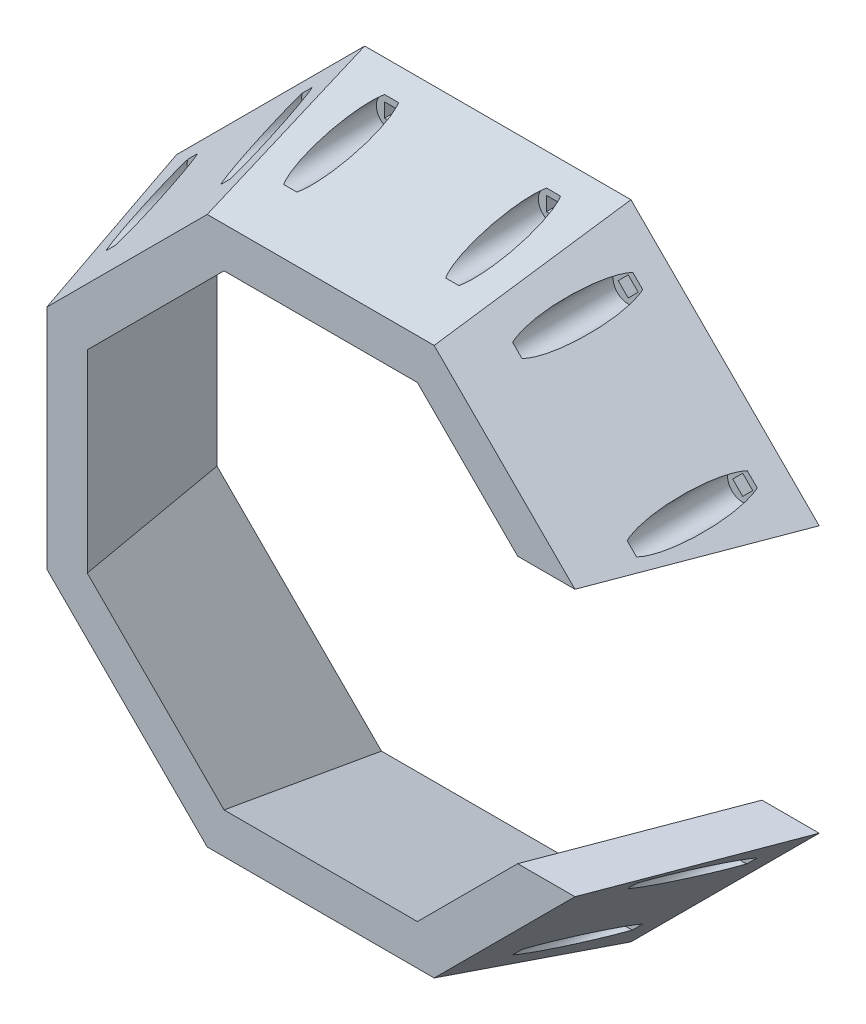
SolidWorks part; units mm, degrees
ref_plane "Plano frontal" through (0, 0, 0) normal (0, 0, 1) x (1, 0, 0)
ref_plane "Plano superior" through (0, 0, 0) normal (0, 1, 0) x (1, 0, 0)
ref_plane "Plano direito" through (0, 0, 0) normal (1, 0, 0) x (0, 0, -1)
sketch "Esboço1" plane through (0, 0, 0) normal (0, 0, 1) x (1, 0, 0)
  line L1 (63.5, -26.3026) -> (63.5, 26.3026)
  line L2 (63.5, 26.3026) -> (26.3026, 63.5)
  line L3 (26.3026, 63.5) -> (-26.3026, 63.5)
  line L4 (-26.3026, 63.5) -> (-63.5, 26.3026)
  line L5 (-63.5, 26.3026) -> (-63.5, -26.3026)
  line L6 (-63.5, -26.3026) -> (-26.3026, -63.5)
  line L7 (-26.3026, -63.5) -> (26.3026, -63.5)
  line L8 (26.3026, -63.5) -> (63.5, -26.3026)
  circle A0 centre (0, 0) radius 63.5 construction
  circle A1 centre (0, 0) radius 61.5 construction
  dimension "D1" = 127
  dimension "D2" = 2
extrude "Ressalto-extrusão1" add sketch "Esboço1" along normal blind 35 draft 15
sketch "Esboço2" plane through (0, 0, 0) normal (0, 0, 1) x (1, 0, 0)
  line L0 (63.5, 0) -> (43.8368, 0) construction
  line L1 (63.5, -26.3026) -> (63.5, 26.3026) construction
  line L3 (24.1735, 26.3026) -> (63.5, 26.3026)
  line L4 (24.1735, 26.3026) -> (24.1735, -26.3026)
  line L5 (24.1735, -26.3026) -> (63.5, -26.3026)
  line L6 (63.5, 26.3026) -> (63.5, -26.3026)
  line L7 (24.1735, 26.3026) -> (63.5, -26.3026) construction
  line L8 (24.1735, -26.3026) -> (63.5, 26.3026) construction
extrude "Corte-extrusão1" cut sketch "Esboço2" along normal blind 50
sketch "Esboço4" plane through (0, 0, 0) normal (0, 0, -1) x (-1, 0, 0)
  line L0 (-44.9013, -44.9013) -> (-42.0729, -42.0729) construction
  line L1 (-47.7297, -34.4361) -> (-49.7096, -36.416)
  line L2 (-42.0729, -40.093) -> (-44.0528, -42.0729)
  line L3 (-42.0729, -40.093) -> (-40.093, -42.0729)
  line L4 (-40.093, -42.0729) -> (-42.0729, -44.0528)
  line L5 (-44.0528, -42.0729) -> (-42.0729, -44.0528)
  line L6 (-42.0729, -40.093) -> (-42.0729, -44.0528) construction
  line L7 (-40.093, -42.0729) -> (-44.0528, -42.0729) construction
  line L8 (-47.7297, -34.4361) -> (-45.7498, -36.416)
  line L9 (-45.7498, -36.416) -> (-47.7297, -38.3959)
  line L10 (-49.7096, -36.416) -> (-47.7297, -38.3959)
  line L11 (-47.7297, -34.4361) -> (-47.7297, -38.3959) construction
  line L12 (-45.7498, -36.416) -> (-49.7096, -36.416) construction
  line L13 (-53.3866, -28.7792) -> (-55.3665, -30.7591)
  line L14 (-53.3866, -28.7792) -> (-51.4067, -30.7591)
  line L15 (-51.4067, -30.7591) -> (-53.3866, -32.739)
  line L16 (-55.3665, -30.7591) -> (-53.3866, -32.739)
  line L17 (-53.3866, -28.7792) -> (-53.3866, -32.739) construction
  line L18 (-51.4067, -30.7591) -> (-55.3665, -30.7591) construction
  line L19 (-60.9, 25.2256) -> (-59.0434, 27.0822)
  line L20 (-57.0635, 25.1023) -> (-59.0434, 27.0822)
  line L21 (-58.1, 6.6) -> (-58.1, 9.4)
  line L22 (-58.1, -1.4) -> (-58.1, 1.4)
  line L23 (-58.1, -1.4) -> (-60.9, -1.4)
  line L24 (-60.9, -1.4) -> (-60.9, 1.4)
  line L25 (-58.1, 1.4) -> (-60.9, 1.4)
  line L26 (-30.7591, -51.4067) -> (-30.7591, -55.3665) construction
  line L27 (-28.7792, -53.3866) -> (-32.739, -53.3866) construction
  line L28 (-36.416, -45.7498) -> (-36.416, -49.7096) construction
  line L29 (-34.4361, -47.7297) -> (-38.3959, -47.7297) construction
  line L30 (-42.0729, -40.093) -> (-42.0729, -44.0528) construction
  line L31 (-40.093, -42.0729) -> (-44.0528, -42.0729) construction
  line L32 (-25.2256, -60.9) -> (-27.0822, -59.0434)
  line L33 (-25.1023, -57.0635) -> (-27.0822, -59.0434)
  line L34 (-58.1, 6.6) -> (-60.9, 6.6)
  line L35 (-30.7591, -55.3665) -> (-32.739, -53.3866)
  line L36 (-30.7591, -51.4067) -> (-32.739, -53.3866)
  line L37 (-28.7792, -53.3866) -> (-30.7591, -51.4067)
  line L38 (-28.7792, -53.3866) -> (-30.7591, -55.3665)
  line L39 (-36.416, -49.7096) -> (-38.3959, -47.7297)
  line L40 (-36.416, -45.7498) -> (-38.3959, -47.7297)
  line L41 (-34.4361, -47.7297) -> (-36.416, -45.7498)
  line L42 (-34.4361, -47.7297) -> (-36.416, -49.7096)
  line L43 (0, -63.5) -> (0, -59.5) construction
  line L44 (-6.6, -58.1) -> (-9.4, -58.1)
  line L45 (1.4, -58.1) -> (-1.4, -58.1)
  line L46 (1.4, -58.1) -> (1.4, -60.9)
  line L47 (1.4, -60.9) -> (-1.4, -60.9)
  line L48 (-1.4, -58.1) -> (-1.4, -60.9)
  line L49 (1.4, -58.1) -> (-1.4, -60.9) construction
  line L50 (1.4, -60.9) -> (-1.4, -58.1) construction
  line L51 (-6.6, -58.1) -> (-6.6, -60.9)
  line L52 (-6.6, -60.9) -> (-9.4, -60.9)
  line L53 (-9.4, -58.1) -> (-9.4, -60.9)
  line L54 (-6.6, -58.1) -> (-9.4, -60.9) construction
  line L55 (-6.6, -60.9) -> (-9.4, -58.1) construction
  line L56 (-14.6, -58.1) -> (-17.4, -58.1)
  line L57 (-14.6, -58.1) -> (-14.6, -60.9)
  line L58 (-14.6, -60.9) -> (-17.4, -60.9)
  line L59 (-17.4, -58.1) -> (-17.4, -60.9)
  line L60 (-14.6, -58.1) -> (-17.4, -60.9) construction
  line L61 (-14.6, -60.9) -> (-17.4, -58.1) construction
  line L62 (-22.6, -58.1) -> (-24.0658, -58.1)
  line L63 (-22.6, -58.1) -> (-22.6, -60.9)
  line L64 (-22.6, -60.9) -> (-25.2256, -60.9)
  line L65 (-60.9, 6.6) -> (-60.9, 9.4)
  line L66 (-58.1, 9.4) -> (-60.9, 9.4)
  line L67 (-58.1, 14.6) -> (-58.1, 17.4)
  line L68 (-58.1, 14.6) -> (-60.9, 14.6)
  line L69 (-60.9, 14.6) -> (-60.9, 17.4)
  line L70 (-58.1, 17.4) -> (-60.9, 17.4)
  line L72 (-26.3026, -63.5) -> (26.3026, -63.5)
  line L73 (26.3026, -63.5) -> (63.5, -26.3026)
  line L74 (-24.0658, -58.1) -> (-25.1023, -57.0635)
  line L75 (-58.1, 22.6) -> (-58.1, 24.0658)
  line L76 (-58.1, 22.6) -> (-60.9, 22.6)
  line L77 (63.5, -26.3026) -> (63.5, 26.3026)
  line L78 (-60.9, 22.6) -> (-60.9, 25.2256)
  line L79 (-58.1, 24.0658) -> (-57.0635, 25.1023)
  line L80 (-58.1, -24.0658) -> (-57.0635, -25.1023)
  line L81 (-60.9, -22.6) -> (-60.9, -25.2256)
  line L82 (-58.1, -22.6) -> (-60.9, -22.6)
  line L83 (-58.1, -22.6) -> (-58.1, -24.0658)
  line L84 (-58.1, -17.4) -> (-60.9, -17.4)
  line L85 (-60.9, -14.6) -> (-60.9, -17.4)
  line L86 (-58.1, -14.6) -> (-60.9, -14.6)
  line L87 (-58.1, -14.6) -> (-58.1, -17.4)
  line L88 (-58.1, -9.4) -> (-60.9, -9.4)
  line L89 (-60.9, -6.6) -> (-60.9, -9.4)
  line L90 (-58.1, -6.6) -> (-60.9, -6.6)
  line L91 (-58.1, -6.6) -> (-58.1, -9.4)
  line L92 (63.5, 26.3026) -> (26.3026, 63.5)
  line L93 (26.3026, 63.5) -> (-26.3026, 63.5)
  line L94 (-57.0635, -25.1023) -> (-59.0434, -27.0822)
  line L95 (-60.9, -25.2256) -> (-59.0434, -27.0822)
  line L96 (-63.5, 0) -> (-59.5, 0) construction
  line L97 (-58.1, -1.4) -> (-60.9, 1.4) construction
  line L98 (-60.9, -1.4) -> (-58.1, 1.4) construction
  line L99 (14.6, -60.9) -> (17.4, -58.1) construction
  line L100 (14.6, -58.1) -> (17.4, -60.9) construction
  line L101 (6.6, -60.9) -> (9.4, -58.1) construction
  line L102 (6.6, -58.1) -> (9.4, -60.9) construction
  line L103 (40.093, -42.0729) -> (44.0528, -42.0729) construction
  line L104 (42.0729, -40.093) -> (42.0729, -44.0528) construction
  line L105 (34.4361, -47.7297) -> (38.3959, -47.7297) construction
  line L106 (36.416, -45.7498) -> (36.416, -49.7096) construction
  line L107 (28.7792, -53.3866) -> (32.739, -53.3866) construction
  line L108 (30.7591, -51.4067) -> (30.7591, -55.3665) construction
  line L109 (-58.1, 6.6) -> (-60.9, 9.4) construction
  line L110 (-60.9, 6.6) -> (-58.1, 9.4) construction
  line L111 (-58.1, 14.6) -> (-60.9, 17.4) construction
  line L112 (51.4067, -30.7591) -> (55.3665, -30.7591) construction
  line L113 (53.3866, -28.7792) -> (53.3866, -32.739) construction
  line L114 (45.7498, -36.416) -> (49.7096, -36.416) construction
  line L115 (47.7297, -34.4361) -> (47.7297, -38.3959) construction
  line L116 (40.093, -42.0729) -> (44.0528, -42.0729) construction
  line L117 (42.0729, -40.093) -> (42.0729, -44.0528) construction
  line L118 (44.9013, -44.9013) -> (42.0729, -42.0729) construction
  line L119 (-60.9, 14.6) -> (-58.1, 17.4) construction
  line L120 (-60.9, -14.6) -> (-58.1, -17.4) construction
  line L121 (-58.1, -14.6) -> (-60.9, -17.4) construction
  line L122 (-60.9, -6.6) -> (-58.1, -9.4) construction
  line L123 (-58.1, -6.6) -> (-60.9, -9.4) construction
  line L124 (25.2256, 60.9) -> (27.0822, 59.0434)
  line L125 (25.1023, 57.0635) -> (27.0822, 59.0434)
  line L126 (24.0658, -58.1) -> (25.1023, -57.0635)
  line L127 (6.6, 58.1) -> (9.4, 58.1)
  line L128 (-1.4, 58.1) -> (1.4, 58.1)
  line L129 (-1.4, 58.1) -> (-1.4, 60.9)
  line L130 (-1.4, 60.9) -> (1.4, 60.9)
  line L131 (22.6, -60.9) -> (25.2256, -60.9)
  line L132 (22.6, -58.1) -> (22.6, -60.9)
  line L133 (22.6, -58.1) -> (24.0658, -58.1)
  line L134 (17.4, -58.1) -> (17.4, -60.9)
  line L135 (14.6, -60.9) -> (17.4, -60.9)
  line L136 (14.6, -58.1) -> (14.6, -60.9)
  line L137 (14.6, -58.1) -> (17.4, -58.1)
  line L138 (9.4, -58.1) -> (9.4, -60.9)
  line L139 (6.6, -60.9) -> (9.4, -60.9)
  line L140 (6.6, -58.1) -> (6.6, -60.9)
  line L141 (6.6, -58.1) -> (9.4, -58.1)
  line L142 (34.4361, -47.7297) -> (36.416, -49.7096)
  line L143 (40.093, -42.0729) -> (42.0729, -44.0528)
  line L144 (42.0729, -40.093) -> (44.0528, -42.0729)
  line L145 (34.4361, -47.7297) -> (36.416, -45.7498)
  line L146 (36.416, -45.7498) -> (38.3959, -47.7297)
  line L147 (36.416, -49.7096) -> (38.3959, -47.7297)
  line L148 (28.7792, -53.3866) -> (30.7591, -55.3665)
  line L149 (28.7792, -53.3866) -> (30.7591, -51.4067)
  line L150 (30.7591, -51.4067) -> (32.739, -53.3866)
  line L151 (30.7591, -55.3665) -> (32.739, -53.3866)
  line L152 (1.4, 58.1) -> (1.4, 60.9)
  line L153 (25.1023, -57.0635) -> (27.0822, -59.0434)
  line L154 (25.2256, -60.9) -> (27.0822, -59.0434)
  line L155 (6.6, 58.1) -> (6.6, 60.9)
  line L156 (6.6, 60.9) -> (9.4, 60.9)
  line L157 (9.4, 58.1) -> (9.4, 60.9)
  line L158 (14.6, 58.1) -> (17.4, 58.1)
  line L159 (55.3665, -30.7591) -> (53.3866, -32.739)
  line L160 (51.4067, -30.7591) -> (53.3866, -32.739)
  line L161 (53.3866, -28.7792) -> (51.4067, -30.7591)
  line L162 (53.3866, -28.7792) -> (55.3665, -30.7591)
  line L163 (49.7096, -36.416) -> (47.7297, -38.3959)
  line L164 (45.7498, -36.416) -> (47.7297, -38.3959)
  line L165 (47.7297, -34.4361) -> (45.7498, -36.416)
  line L166 (44.0528, -42.0729) -> (42.0729, -44.0528)
  line L167 (42.0729, -40.093) -> (40.093, -42.0729)
  line L168 (47.7297, -34.4361) -> (49.7096, -36.416)
  line L169 (44.9013, 44.9013) -> (42.0729, 42.0729) construction
  line L170 (42.0729, 40.093) -> (42.0729, 44.0528) construction
  line L171 (40.093, 42.0729) -> (44.0528, 42.0729) construction
  line L172 (47.7297, 34.4361) -> (47.7297, 38.3959) construction
  line L173 (45.7498, 36.416) -> (49.7096, 36.416) construction
  line L174 (53.3866, 28.7792) -> (53.3866, 32.739) construction
  line L175 (51.4067, 30.7591) -> (55.3665, 30.7591) construction
  line L176 (14.6, 58.1) -> (14.6, 60.9)
  line L177 (14.6, 60.9) -> (17.4, 60.9)
  line L178 (30.7591, 51.4067) -> (30.7591, 55.3665) construction
  line L179 (28.7792, 53.3866) -> (32.739, 53.3866) construction
  line L180 (36.416, 45.7498) -> (36.416, 49.7096) construction
  line L181 (34.4361, 47.7297) -> (38.3959, 47.7297) construction
  line L182 (42.0729, 40.093) -> (42.0729, 44.0528) construction
  line L183 (40.093, 42.0729) -> (44.0528, 42.0729) construction
  line L184 (17.4, 58.1) -> (17.4, 60.9)
  line L185 (22.6, 58.1) -> (24.0658, 58.1)
  line L186 (22.6, 58.1) -> (22.6, 60.9)
  line L187 (22.6, 60.9) -> (25.2256, 60.9)
  line L188 (24.0658, 58.1) -> (25.1023, 57.0635)
  line L189 (-24.0658, 58.1) -> (-25.1023, 57.0635)
  line L190 (-22.6, 60.9) -> (-25.2256, 60.9)
  line L191 (-22.6, 58.1) -> (-22.6, 60.9)
  line L192 (-22.6, 58.1) -> (-24.0658, 58.1)
  line L193 (-17.4, 58.1) -> (-17.4, 60.9)
  line L194 (-14.6, 60.9) -> (-17.4, 60.9)
  line L195 (-14.6, 58.1) -> (-14.6, 60.9)
  line L196 (-14.6, 58.1) -> (-17.4, 58.1)
  line L197 (-9.4, 58.1) -> (-9.4, 60.9)
  line L198 (-6.6, 60.9) -> (-9.4, 60.9)
  line L199 (-6.6, 58.1) -> (-6.6, 60.9)
  line L200 (-6.6, 58.1) -> (-9.4, 58.1)
  line L201 (-25.1023, 57.0635) -> (-27.0822, 59.0434)
  line L202 (-25.2256, 60.9) -> (-27.0822, 59.0434)
  line L203 (-40.093, 42.0729) -> (-44.0528, 42.0729) construction
  line L204 (-42.0729, 40.093) -> (-42.0729, 44.0528) construction
  line L205 (-34.4361, 47.7297) -> (-38.3959, 47.7297) construction
  line L206 (-36.416, 45.7498) -> (-36.416, 49.7096) construction
  line L207 (-28.7792, 53.3866) -> (-32.739, 53.3866) construction
  line L208 (-30.7591, 51.4067) -> (-30.7591, 55.3665) construction
  line L209 (0, 63.5) -> (0, 59.5) construction
  line L210 (-1.4, 58.1) -> (1.4, 60.9) construction
  line L211 (-51.4067, 30.7591) -> (-55.3665, 30.7591) construction
  line L212 (-53.3866, 28.7792) -> (-53.3866, 32.739) construction
  line L213 (-45.7498, 36.416) -> (-49.7096, 36.416) construction
  line L214 (-47.7297, 34.4361) -> (-47.7297, 38.3959) construction
  line L215 (-40.093, 42.0729) -> (-44.0528, 42.0729) construction
  line L216 (-42.0729, 40.093) -> (-42.0729, 44.0528) construction
  line L217 (-44.9013, 44.9013) -> (-42.0729, 42.0729) construction
  line L218 (47.7297, 34.4361) -> (49.7096, 36.416)
  line L219 (42.0729, 40.093) -> (44.0528, 42.0729)
  line L220 (42.0729, 40.093) -> (40.093, 42.0729)
  line L221 (40.093, 42.0729) -> (42.0729, 44.0528)
  line L222 (44.0528, 42.0729) -> (42.0729, 44.0528)
  line L223 (47.7297, 34.4361) -> (45.7498, 36.416)
  line L224 (45.7498, 36.416) -> (47.7297, 38.3959)
  line L225 (49.7096, 36.416) -> (47.7297, 38.3959)
  line L226 (53.3866, 28.7792) -> (55.3665, 30.7591)
  line L227 (53.3866, 28.7792) -> (51.4067, 30.7591)
  line L228 (51.4067, 30.7591) -> (53.3866, 32.739)
  line L229 (55.3665, 30.7591) -> (53.3866, 32.739)
  line L230 (-1.4, 60.9) -> (1.4, 58.1) construction
  line L231 (6.6, 58.1) -> (9.4, 60.9) construction
  line L232 (6.6, 60.9) -> (9.4, 58.1) construction
  line L233 (14.6, 58.1) -> (17.4, 60.9) construction
  line L234 (14.6, 60.9) -> (17.4, 58.1) construction
  line L235 (-14.6, 60.9) -> (-17.4, 58.1) construction
  line L236 (-14.6, 58.1) -> (-17.4, 60.9) construction
  line L237 (30.7591, 55.3665) -> (32.739, 53.3866)
  line L238 (30.7591, 51.4067) -> (32.739, 53.3866)
  line L239 (28.7792, 53.3866) -> (30.7591, 51.4067)
  line L240 (28.7792, 53.3866) -> (30.7591, 55.3665)
  line L241 (36.416, 49.7096) -> (38.3959, 47.7297)
  line L242 (36.416, 45.7498) -> (38.3959, 47.7297)
  line L243 (34.4361, 47.7297) -> (36.416, 45.7498)
  line L244 (34.4361, 47.7297) -> (36.416, 49.7096)
  line L245 (-6.6, 60.9) -> (-9.4, 58.1) construction
  line L246 (-6.6, 58.1) -> (-9.4, 60.9) construction
  line L247 (60.9, -25.2256) -> (59.0434, -27.0822)
  line L248 (57.0635, -25.1023) -> (59.0434, -27.0822)
  line L249 (58.1, -6.6) -> (58.1, -9.4)
  line L250 (58.1, 1.4) -> (58.1, -1.4)
  line L251 (58.1, 1.4) -> (60.9, 1.4)
  line L252 (60.9, 1.4) -> (60.9, -1.4)
  line L253 (58.1, -1.4) -> (60.9, -1.4)
  line L254 (58.1, -6.6) -> (60.9, -6.6)
  line L255 (60.9, -6.6) -> (60.9, -9.4)
  line L256 (58.1, -9.4) -> (60.9, -9.4)
  line L257 (58.1, -14.6) -> (58.1, -17.4)
  line L258 (58.1, -14.6) -> (60.9, -14.6)
  line L259 (60.9, -14.6) -> (60.9, -17.4)
  line L260 (58.1, -17.4) -> (60.9, -17.4)
  line L261 (58.1, -22.6) -> (58.1, -24.0658)
  line L262 (58.1, -22.6) -> (60.9, -22.6)
  line L263 (60.9, -22.6) -> (60.9, -25.2256)
  line L264 (58.1, -24.0658) -> (57.0635, -25.1023)
  line L265 (58.1, 24.0658) -> (57.0635, 25.1023)
  line L266 (60.9, 22.6) -> (60.9, 25.2256)
  line L267 (58.1, 22.6) -> (60.9, 22.6)
  line L268 (58.1, 22.6) -> (58.1, 24.0658)
  line L269 (58.1, 17.4) -> (60.9, 17.4)
  line L270 (60.9, 14.6) -> (60.9, 17.4)
  line L271 (58.1, 14.6) -> (60.9, 14.6)
  line L272 (58.1, 14.6) -> (58.1, 17.4)
  line L273 (58.1, 9.4) -> (60.9, 9.4)
  line L274 (60.9, 6.6) -> (60.9, 9.4)
  line L275 (58.1, 6.6) -> (60.9, 6.6)
  line L276 (58.1, 6.6) -> (58.1, 9.4)
  line L277 (57.0635, 25.1023) -> (59.0434, 27.0822)
  line L278 (60.9, 25.2256) -> (59.0434, 27.0822)
  line L279 (63.5, 0) -> (59.5, 0) construction
  line L280 (58.1, 1.4) -> (60.9, -1.4) construction
  line L281 (60.9, 1.4) -> (58.1, -1.4) construction
  line L282 (58.1, -6.6) -> (60.9, -9.4) construction
  line L283 (60.9, -6.6) -> (58.1, -9.4) construction
  line L284 (58.1, -14.6) -> (60.9, -17.4) construction
  line L285 (60.9, -14.6) -> (58.1, -17.4) construction
  line L286 (60.9, 14.6) -> (58.1, 17.4) construction
  line L287 (-34.4361, 47.7297) -> (-36.416, 49.7096)
  line L288 (-40.093, 42.0729) -> (-42.0729, 44.0528)
  line L289 (-42.0729, 40.093) -> (-44.0528, 42.0729)
  line L290 (-34.4361, 47.7297) -> (-36.416, 45.7498)
  line L291 (-36.416, 45.7498) -> (-38.3959, 47.7297)
  line L292 (-36.416, 49.7096) -> (-38.3959, 47.7297)
  line L293 (-28.7792, 53.3866) -> (-30.7591, 55.3665)
  line L294 (-28.7792, 53.3866) -> (-30.7591, 51.4067)
  line L295 (-30.7591, 51.4067) -> (-32.739, 53.3866)
  line L296 (-30.7591, 55.3665) -> (-32.739, 53.3866)
  line L297 (58.1, 14.6) -> (60.9, 17.4) construction
  line L298 (60.9, 6.6) -> (58.1, 9.4) construction
  line L299 (58.1, 6.6) -> (60.9, 9.4) construction
  line L300 (-26.3026, 63.5) -> (-63.5, 26.3026)
  line L301 (-63.5, 26.3026) -> (-63.5, -26.3026)
  line L302 (-63.5, -26.3026) -> (-26.3026, -63.5)
  line L303 (-22.9889, 55.5) -> (-55.5, 22.9889)
  line L304 (-55.3665, 30.7591) -> (-53.3866, 32.739)
  line L305 (-51.4067, 30.7591) -> (-53.3866, 32.739)
  line L306 (-53.3866, 28.7792) -> (-51.4067, 30.7591)
  line L307 (-53.3866, 28.7792) -> (-55.3665, 30.7591)
  line L308 (-49.7096, 36.416) -> (-47.7297, 38.3959)
  line L309 (-45.7498, 36.416) -> (-47.7297, 38.3959)
  line L310 (-47.7297, 34.4361) -> (-45.7498, 36.416)
  line L311 (-44.0528, 42.0729) -> (-42.0729, 44.0528)
  line L312 (-42.0729, 40.093) -> (-40.093, 42.0729)
  line L313 (-47.7297, 34.4361) -> (-49.7096, 36.416)
  line L314 (-55.5, 22.9889) -> (-55.5, -22.9889)
  line L315 (-55.5, -22.9889) -> (-22.9889, -55.5)
  line L316 (-22.9889, -55.5) -> (22.9889, -55.5)
  line L317 (22.9889, -55.5) -> (55.5, -22.9889)
  line L318 (55.5, -22.9889) -> (55.5, 22.9889)
  line L319 (55.5, 22.9889) -> (22.9889, 55.5)
  line L320 (22.9889, 55.5) -> (-22.9889, 55.5)
  circle A0 centre (0, 0) radius 63.5 construction
  circle A1 centre (0, 0) radius 55.5 construction
  point P2 (-42.0729, -42.0729)
  point P8 (-47.7297, -36.416)
  point P13 (-53.3866, -30.7591)
  point P35 (-30.7591, -53.3866)
  point P36 (-36.416, -47.7297)
  point P39 (0, -59.5)
  point P44 (-8, -59.5)
  point P49 (-16, -59.5)
  point P58 (-59.5, 0)
  point P64 (-59.5, 8)
  point P71 (-59.5, 16)
  point P95 (-59.5, -24)
  point P116 (-59.5, -16)
  point P117 (-59.5, -8)
  point P118 (-59.0434, -25.1023)
  point P139 (0, 59.5)
  point P140 (24, -59.5)
  point P141 (16, -59.5)
  point P142 (8, -59.5)
  point P143 (36.416, -47.7297)
  point P144 (30.7591, -53.3866)
  point P145 (25.1023, -59.0434)
  point P147 (53.3866, -30.7591)
  point P148 (47.7297, -36.416)
  point P166 (8, 59.5)
  point P179 (16, 59.5)
  point P202 (-24, 59.5)
  point P203 (-16, 59.5)
  point P204 (-8, 59.5)
  point P205 (-25.1023, 59.0434)
  point P210 (59.5, 0)
  point P227 (59.5, -8)
  point P242 (59.5, -16)
  point P250 (47.7297, 36.416)
  point P251 (53.3866, 30.7591)
  point P254 (30.7591, 53.3866)
  point P255 (36.416, 47.7297)
  point P266 (-36.416, 47.7297)
  point P267 (-30.7591, 53.3866)
  point P270 (-53.3866, 30.7591)
  point P271 (-47.7297, 36.416)
  point P276 (59.5, 24)
  point P277 (59.5, 16)
  point P278 (59.5, 8)
  point P297 (59.0434, 25.1023)
  dimension "D1" = 4
sketch "Esboço5" plane through (0, 0, 0) normal (0, 0, -1) x (-1, 0, 0)
  line L1 (-17.4, 60.9) -> (-14.6, 60.9)
  line L2 (-17.4, 60.9) -> (-17.4, 58.1)
  line L3 (-17.4, 58.1) -> (-14.6, 58.1)
  line L4 (-14.6, 60.9) -> (-14.6, 58.1)
  line L5 (-17.4, 60.9) -> (-14.6, 58.1) construction
  line L6 (-17.4, 58.1) -> (-14.6, 60.9) construction
  line L7 (-14.6, 58.1) -> (-17.4, 60.9) construction
  line L8 (30.7591, 55.3665) -> (32.739, 53.3866)
  line L9 (14.6, 60.9) -> (17.4, 60.9)
  line L10 (14.6, 60.9) -> (14.6, 58.1)
  line L11 (14.6, 58.1) -> (17.4, 58.1)
  line L12 (17.4, 60.9) -> (17.4, 58.1)
  line L13 (14.6, 60.9) -> (17.4, 58.1) construction
  line L14 (14.6, 58.1) -> (17.4, 60.9) construction
  line L15 (30.7591, 55.3665) -> (28.7792, 53.3866)
  line L16 (28.7792, 53.3866) -> (30.7591, 51.4067)
  line L17 (32.739, 53.3866) -> (30.7591, 51.4067)
  line L18 (53.3866, 32.739) -> (55.3665, 30.7591)
  line L19 (53.3866, 32.739) -> (51.4067, 30.7591)
  line L20 (51.4067, 30.7591) -> (53.3866, 28.7792)
  line L21 (55.3665, 30.7591) -> (53.3866, 28.7792)
  line L22 (30.7591, 55.3665) -> (30.7591, 51.4067) construction
  line L23 (28.7792, 53.3866) -> (32.739, 53.3866) construction
  line L24 (53.3866, 32.739) -> (53.3866, 28.7792) construction
  line L25 (51.4067, 30.7591) -> (55.3665, 30.7591) construction
  line L26 (60.9, 17.4) -> (60.9, 14.6)
  line L27 (60.9, 17.4) -> (58.1, 17.4)
  line L28 (58.1, 17.4) -> (58.1, 14.6)
  line L29 (60.9, 14.6) -> (58.1, 14.6)
  line L30 (60.9, -14.6) -> (60.9, -17.4)
  line L31 (60.9, -14.6) -> (58.1, -14.6)
  line L32 (58.1, -14.6) -> (58.1, -17.4)
  line L33 (60.9, -17.4) -> (58.1, -17.4)
  line L34 (60.9, 17.4) -> (58.1, 14.6) construction
  line L35 (58.1, 17.4) -> (60.9, 14.6) construction
  line L36 (60.9, -14.6) -> (58.1, -17.4) construction
  line L37 (58.1, -14.6) -> (60.9, -17.4) construction
  line L38 (55.3665, -30.7591) -> (53.3866, -32.739)
  line L39 (55.3665, -30.7591) -> (53.3866, -28.7792)
  line L40 (53.3866, -28.7792) -> (51.4067, -30.7591)
  line L41 (53.3866, -32.739) -> (51.4067, -30.7591)
  line L42 (32.739, -53.3866) -> (30.7591, -55.3665)
  line L43 (32.739, -53.3866) -> (30.7591, -51.4067)
  line L44 (30.7591, -51.4067) -> (28.7792, -53.3866)
  line L45 (30.7591, -55.3665) -> (28.7792, -53.3866)
  line L46 (55.3665, -30.7591) -> (51.4067, -30.7591) construction
  line L47 (53.3866, -28.7792) -> (53.3866, -32.739) construction
  line L48 (32.739, -53.3866) -> (28.7792, -53.3866) construction
  line L49 (30.7591, -51.4067) -> (30.7591, -55.3665) construction
  line L50 (17.4, -60.9) -> (14.6, -60.9)
  line L51 (17.4, -60.9) -> (17.4, -58.1)
  line L52 (17.4, -58.1) -> (14.6, -58.1)
  line L53 (14.6, -60.9) -> (14.6, -58.1)
  line L54 (-14.6, -60.9) -> (-17.4, -60.9)
  line L55 (-14.6, -60.9) -> (-14.6, -58.1)
  line L56 (-14.6, -58.1) -> (-17.4, -58.1)
  line L57 (-17.4, -60.9) -> (-17.4, -58.1)
  line L58 (17.4, -60.9) -> (14.6, -58.1) construction
  line L59 (17.4, -58.1) -> (14.6, -60.9) construction
  line L60 (-14.6, -60.9) -> (-17.4, -58.1) construction
  line L61 (-14.6, -58.1) -> (-17.4, -60.9) construction
  line L62 (-30.7591, -55.3665) -> (-32.739, -53.3866)
  line L63 (-30.7591, -55.3665) -> (-28.7792, -53.3866)
  line L64 (-28.7792, -53.3866) -> (-30.7591, -51.4067)
  line L65 (-32.739, -53.3866) -> (-30.7591, -51.4067)
  line L66 (-53.3866, -32.739) -> (-55.3665, -30.7591)
  line L67 (-53.3866, -32.739) -> (-51.4067, -30.7591)
  line L68 (-51.4067, -30.7591) -> (-53.3866, -28.7792)
  line L69 (-55.3665, -30.7591) -> (-53.3866, -28.7792)
  line L70 (-30.7591, -55.3665) -> (-30.7591, -51.4067) construction
  line L71 (-28.7792, -53.3866) -> (-32.739, -53.3866) construction
  line L72 (-53.3866, -32.739) -> (-53.3866, -28.7792) construction
  line L73 (-51.4067, -30.7591) -> (-55.3665, -30.7591) construction
  line L74 (-60.9, -17.4) -> (-60.9, -14.6)
  line L75 (-60.9, -17.4) -> (-58.1, -17.4)
  line L76 (-58.1, -17.4) -> (-58.1, -14.6)
  line L77 (-60.9, -14.6) -> (-58.1, -14.6)
  line L78 (-60.9, 14.6) -> (-60.9, 17.4)
  line L79 (-60.9, 14.6) -> (-58.1, 14.6)
  line L80 (-58.1, 14.6) -> (-58.1, 17.4)
  line L81 (-60.9, 17.4) -> (-58.1, 17.4)
  line L82 (-60.9, -17.4) -> (-58.1, -14.6) construction
  line L83 (-58.1, -17.4) -> (-60.9, -14.6) construction
  line L84 (-60.9, 14.6) -> (-58.1, 17.4) construction
  line L85 (-58.1, 14.6) -> (-60.9, 17.4) construction
  line L86 (-55.3665, 30.7591) -> (-53.3866, 32.739)
  line L87 (-55.3665, 30.7591) -> (-53.3866, 28.7792)
  line L88 (-53.3866, 28.7792) -> (-51.4067, 30.7591)
  line L89 (-53.3866, 32.739) -> (-51.4067, 30.7591)
  line L90 (-32.739, 53.3866) -> (-30.7591, 55.3665)
  line L91 (-32.739, 53.3866) -> (-30.7591, 51.4067)
  line L92 (-30.7591, 51.4067) -> (-28.7792, 53.3866)
  line L93 (-30.7591, 55.3665) -> (-28.7792, 53.3866)
  line L94 (-55.3665, 30.7591) -> (-51.4067, 30.7591) construction
  line L95 (-53.3866, 28.7792) -> (-53.3866, 32.739) construction
  line L96 (-32.739, 53.3866) -> (-28.7792, 53.3866) construction
  line L97 (-30.7591, 51.4067) -> (-30.7591, 55.3665) construction
  point P0 (-16, 59.5)
  point P9 (16, 59.5)
  point P19 (30.7591, 53.3866)
  point P24 (53.3866, 30.7591)
  point P29 (59.5, 16)
  point P34 (59.5, -16)
  point P39 (53.3866, -30.7591)
  point P44 (30.7591, -53.3866)
  point P49 (16, -59.5)
  point P54 (-16, -59.5)
  point P59 (-30.7591, -53.3866)
  point P64 (-53.3866, -30.7591)
  point P69 (-59.5, -16)
  point P74 (-59.5, 16)
  point P79 (-53.3866, 30.7591)
  point P84 (-30.7591, 53.3866)
  point P89 (0, 0)
extrude "Corte-extrusão2" cut sketch "Esboço5" against normal through all
sketch "Esboço6" plane through (0, 0, 0) normal (0, 0, -1) x (-1, 0, 0)
  circle A0 centre (-16, 59.5) radius 3
  circle A1 centre (16, 59.5) radius 3
  circle A2 centre (30.7591, 53.3866) radius 3
  circle A3 centre (53.3866, 30.7591) radius 3
  circle A4 centre (59.5, 16) radius 3
  circle A5 centre (59.5, -16) radius 3
  circle A6 centre (53.3866, -30.7591) radius 3
  circle A7 centre (30.7591, -53.3866) radius 3
  circle A8 centre (16, -59.5) radius 3
  circle A9 centre (-16, -59.5) radius 3
  circle A10 centre (-30.7591, -53.3866) radius 3
  circle A11 centre (-53.3866, -30.7591) radius 3
  circle A12 centre (-59.5, -16) radius 3
  circle A13 centre (-59.5, 16) radius 3
  circle A14 centre (-53.3866, 30.7591) radius 3
  circle A15 centre (-30.7591, 53.3866) radius 3
  point P36 (0, 0)
extrude "Corte-extrusão3" cut sketch "Esboço6" against normal blind 20 from offset 5 offset against normal yes
sketch "Esboço9" plane through (0, 0, 0) normal (0, 0, -1) x (-1, 0, 0)
  line L1 (22.9889, 55.5) -> (-22.9889, 55.5)
  line L2 (-22.9889, 55.5) -> (-55.5, 22.9889)
  line L3 (-55.5, 22.9889) -> (-55.5, -22.9889)
  line L4 (-55.5, -22.9889) -> (-22.9889, -55.5)
  line L5 (-22.9889, -55.5) -> (22.9889, -55.5)
  line L6 (22.9889, -55.5) -> (55.5, -22.9889)
  line L7 (55.5, -22.9889) -> (55.5, 22.9889)
  line L8 (55.5, 22.9889) -> (22.9889, 55.5)
  circle A0 centre (0, 0) radius 55.5 construction
  dimension "D1" = 111
extrude "Corte-extrusão4" cut sketch "Esboço9" against normal up to surface (35 mm away) draft 15 up to face at (4.0578, 0, 35)
